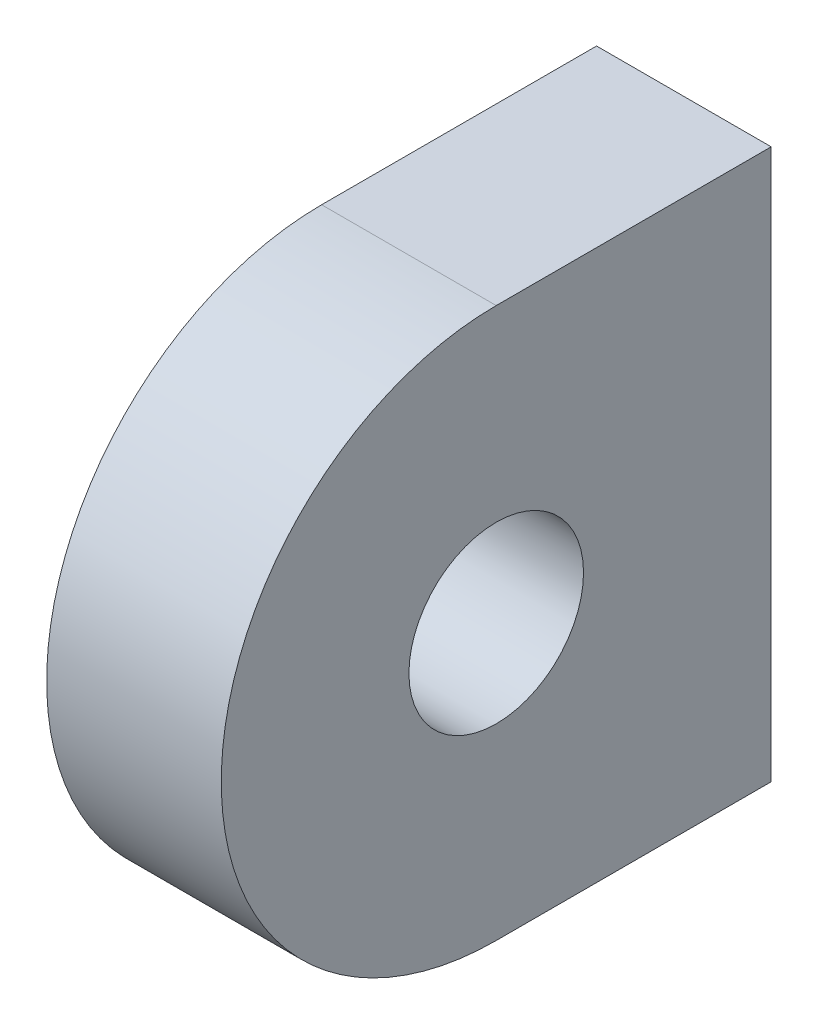
SolidWorks part; units mm, degrees
ref_plane "Front Plane" through (0, 0, 0) normal (0, 0, 1) x (1, 0, 0)
ref_plane "Top Plane" through (0, 0, 0) normal (0, 1, 0) x (1, 0, 0)
ref_plane "Right Plane" through (0, 0, 0) normal (1, 0, 0) x (0, 0, -1)
sketch "Sketch1" plane through (0, 0, 0) normal (1, 0, 0) x (0, 0, -1)
  line L0 (0, 10) -> (10, 10)
  line L1 (10, 10) -> (10, -10)
  line L2 (10, -10) -> (0, -10)
  arc A0 (0, 10) -> (0, -10) centre (0, 0) ccw
  circle A1 centre (0, 0) radius 3.175
extrude "Boss-Extrude1" add sketch "Sketch1" along normal blind 6.35
